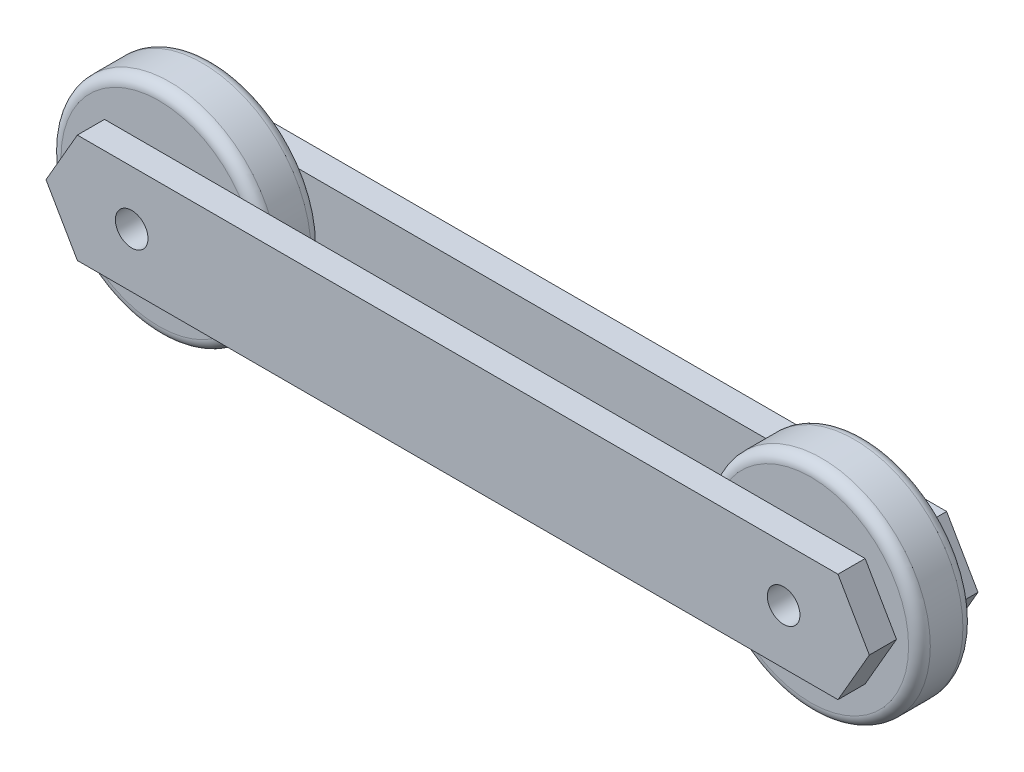
SolidWorks part; units mm, degrees
ref_plane "Front Plane" through (0, 0, 0) normal (0, 0, 1) x (1, 0, 0)
ref_plane "Top Plane" through (0, 0, 0) normal (0, 1, 0) x (1, 0, 0)
ref_plane "Right Plane" through (0, 0, 0) normal (1, 0, 0) x (0, 0, -1)
sketch "Sketch1" plane through (0, 0, 0) normal (0, 0, 1) x (1, 0, 0)
  line L1 (28.8675, 50) -> (0, 100)
  line L2 (0, 100) -> (-700, 100)
  line L3 (-700, 100) -> (-728.8675, 50)
  line L4 (-728.8675, 50) -> (-700, 0)
  line L5 (-700, 0) -> (0, 0)
  line L6 (0, 0) -> (28.8675, 50)
  circle A0 centre (-650, 50) radius 15
  circle A1 centre (-50, 50) radius 15
  dimension "D10" = 30
  dimension "D1" = 120
  dimension "D2" = 120
  dimension "D3" = 120
  dimension "D4" = 120
  dimension "D5" = 120
  dimension "D6" = 700
  dimension "D7" = 100
  dimension "D8" = 50
  dimension "D9" = 50
extrude "Boss-Extrude1" add sketch "Sketch1" against normal mid plane 25
ref_plane "Plane1" through (0, 0, -37.5) normal (0, 0, -1) x (-1, 0, 0)
mirror "Mirror6" about plane through (0, 0, -37.5) normal (0, 0, -1) of bodies 101
sketch "Sketch2" plane through (0, 0, -62.5) normal (0, 0, 1) x (1, 0, 0)
  circle A0 centre (-650, 50) radius 40
  circle A1 centre (-50, 50) radius 40
  dimension "D1" = 80
  dimension "D2" = 80
extrude "Boss-Extrude2" add sketch "Sketch2" along normal up to surface (50 mm away) up to face at (-35, 50, -12.5)
sketch "Sketch3" plane through (0, 0, -37.5) normal (0, 0, -1) x (-1, 0, 0)
  circle A0 centre (50, 50) radius 100
  circle A1 centre (650, 50) radius 100
  dimension "D1" = 200
  dimension "D2" = 200
extrude "Boss-Extrude3" add sketch "Sketch3" along normal mid plane 50 separate body
fillet "Fillet1" radius 10 2 edges at (-150, 50, -12.5) (-150, 50, -62.5)
fillet "Fillet2" radius 10 2 edges at (-750, 50, -12.5) (-750, 50, -62.5)
sketch "Sketch4" plane through (0, 0, -37.5) normal (0, 0, -1) x (-1, 0, 0)
  point P0 (50, 50)
  point P1 (650, 50)
